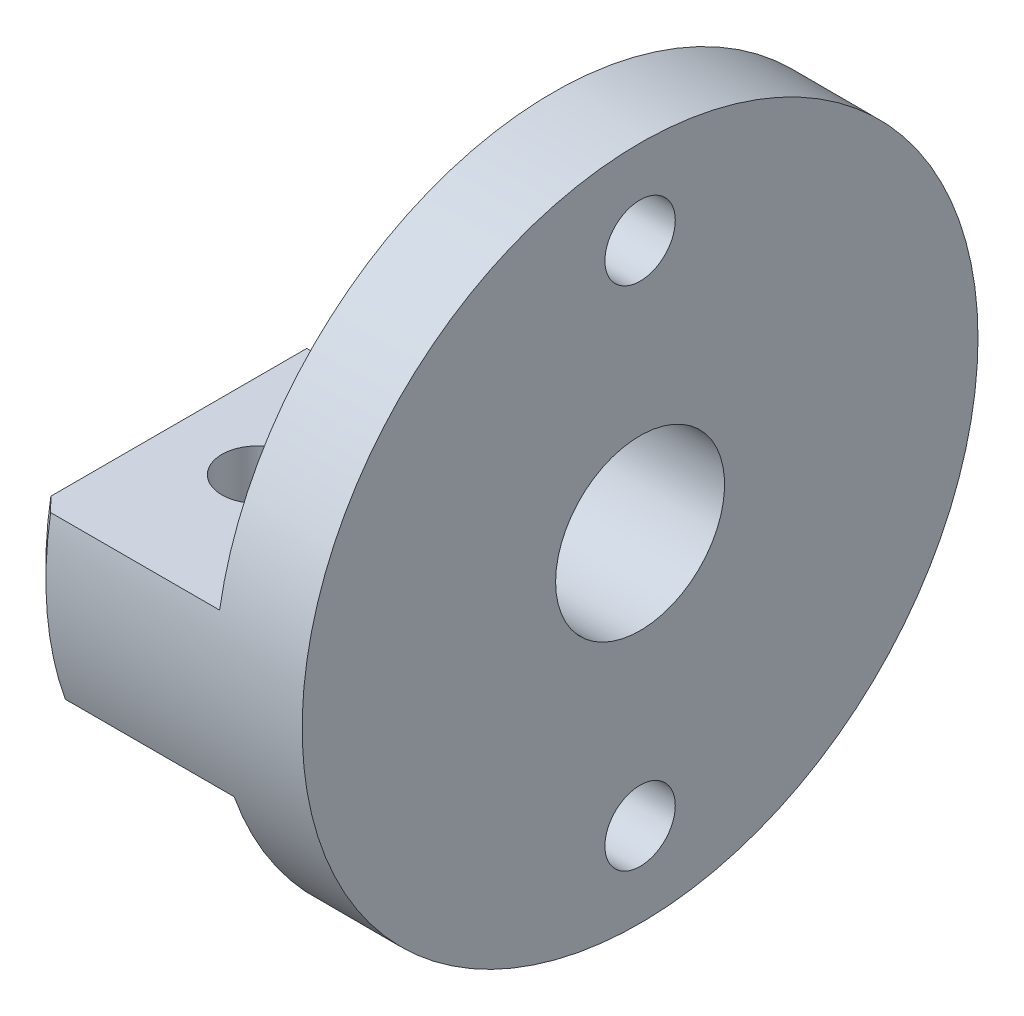
SolidWorks part; units mm, degrees
material "6061-T6 (SS)"
ref_plane "前视基准面" through (0, 0, 0) normal (0, 0, 1) x (1, 0, 0)
ref_plane "上视基准面" through (0, 0, 0) normal (0, 1, 0) x (1, 0, 0)
ref_plane "右视基准面" through (0, 0, 0) normal (1, 0, 0) x (0, 0, -1)
sketch "草图1" plane through (0, 0, 0) normal (1, 0, 0) x (0, 0, -1)
  circle A0 centre (0, 0) radius 12
  dimension "D1" = 24
extrude "凸台-拉伸1" add sketch "草图1" along normal blind 6
sketch "草图2" plane through (6, 0, 0) normal (1, 0, 0) x (0, 0, -1)
  circle A0 centre (0, 0) radius 12
  dimension "D1" = 24
extrude "凸台-拉伸2" add sketch "草图2" along normal blind 3.6
sketch "草图3" plane through (0, 0, 0) normal (-1, 0, 0) x (0, 0, 1)
  circle A0 centre (0, 0) radius 3
  dimension "D1" = 6
extrude "切除-拉伸1" cut sketch "草图3" against normal through all
sketch "草图4" plane through (0, 0, 0) normal (-1, 0, 0) x (0, 0, 1)
  line L0 (-11.8322, 2) -> (11.8322, 2)
  line L1 (11.3137, -4) -> (-11.3137, -4)
  circle A0 centre (0, 0) radius 12 construction
  arc A2 (-11.3137, -4) -> (11.3137, -4) centre (0, 0) ccw
  arc A3 (11.8322, 2) -> (-11.8322, 2) centre (0, 0) ccw
  circle A4 centre (0, 0) radius 3 construction
  dimension "D1" = 4
  dimension "D2" = 2
extrude "切除-拉伸2" cut sketch "草图4" against normal blind 6
chamfer "倒角1" distance 0.5 angle 45 2 edges at (0, -1.0331, 11.9555) (0, -1.0331, -11.9555)
sketch "草图5" plane through (0, -4, 0) normal (0, -1, 0) x (1, 0, 0)
  line L0 (6, 0) -> (0, 0) construction
  line L1 (6, 11.3137) -> (6, -11.3137) construction
  line L2 (0, 10.7819) -> (0, -10.7819) construction
  circle A0 centre (3, -7) radius 1.25
  circle A1 centre (3, 7) radius 1.25
  circle A2 centre (3, 0) radius 1.5 construction
  dimension "D1" = 3
  dimension "D2" = 2.5
  dimension "D3" = 7
  dimension "D4" = 3
  dimension "D5" = 3
extrude "切除-拉伸3" cut sketch "草图5" against normal through all
cosmetic thread "孔螺蚊线1" parameters "D2"=3
cosmetic thread "孔螺蚊线2" parameters "D2"=3
cosmetic thread "孔螺蚊线3" parameters "D2"=3
cosmetic thread "孔螺蚊线4" parameters "D2"=3
sketch "草图8" plane through (9.6, 0, 0) normal (1, 0, 0) x (0, 0, -1)
  line L0 (0, 12) -> (0, 0) construction
  circle A0 centre (0, 0) radius 12 construction
  circle A1 centre (0, 9) radius 1.25
  circle A3 centre (0, -9) radius 1.25
  circle A5 centre (9, 0) radius 1.25 [skipped]
  circle A6 centre (-9, 0) radius 1.25 [skipped]
  point P16 (0, 0)
  dimension "D1" = 2.5
  dimension "D2" = 9
  dimension "D3" = 4
sketch "草图12" plane through (6, 0, 0) normal (-1, 0, 0) x (0, 0, 1)
  line L0 (11.3137, -4) -> (-11.3137, -4) construction
  line L1 (2.2361, 2) -> (11.8322, 2) construction
  line L2 (-11.8322, 2) -> (-2.2361, 2) construction
  line L3 (11.3137, -4) -> (-11.3137, -4)
  line L4 (2.2361, 2) -> (11.8322, 2)
  line L5 (-11.8322, 2) -> (-2.2361, 2)
  arc A0 (-11.3137, -4) -> (11.3137, -4) centre (0, 0) ccw construction
  arc A1 (2.2361, 2) -> (-2.2361, 2) centre (0, 0) ccw construction
  arc A2 (11.8322, 2) -> (-11.8322, 2) centre (0, 0) ccw construction
  arc A3 (-11.3137, -4) -> (11.3137, -4) centre (0, 0) ccw
  arc A4 (2.2361, 2) -> (-2.2361, 2) centre (0, 0) ccw
  arc A5 (11.8322, 2) -> (-11.8322, 2) centre (0, 0) ccw
extrude "切除-拉伸7" cut sketch "草图12" against normal blind 0.5
sketch "草图13" plane through (0, -4, 0) normal (0, -1, 0) x (-1, 0, 0)
  line L0 (0, -10.7819) -> (0, 10.7819) construction
  circle A0 centre (-2.6, 0) radius 1.25
  dimension "D1" = 2.6
  dimension "D2" = 2.5
extrude "切除-拉伸8" cut sketch "草图13" against normal through all
extrude "切除-拉伸9" cut sketch "草图8" against normal through all
